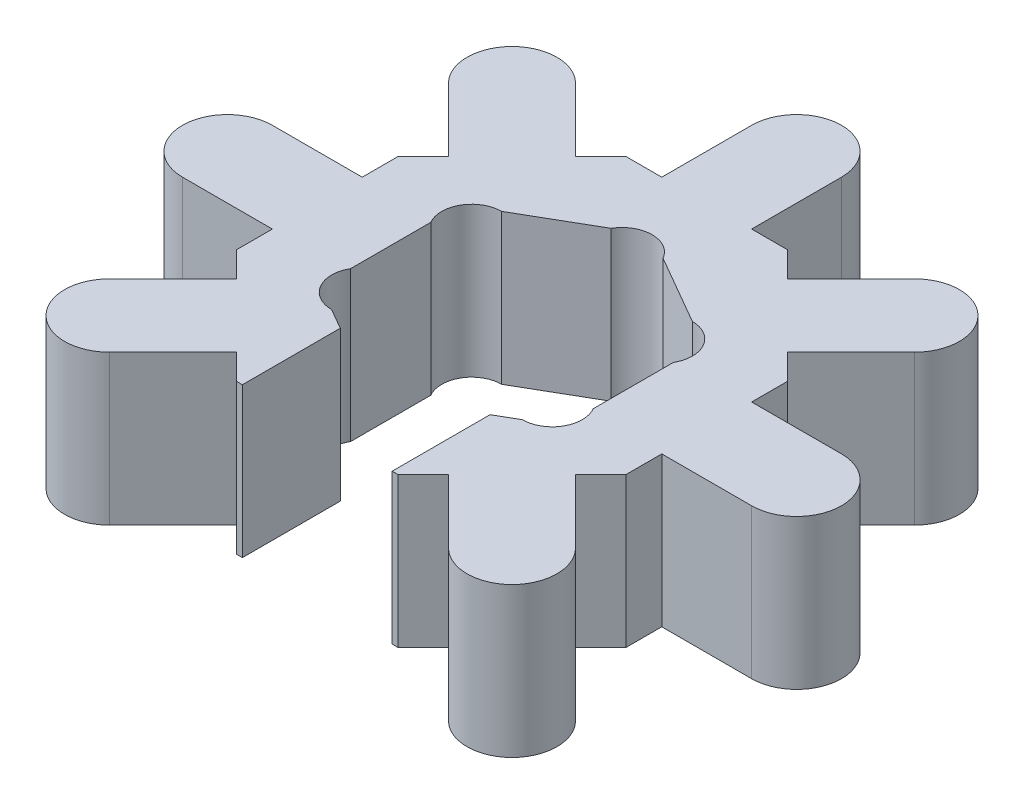
SolidWorks part; units mm, degrees
ref_plane "정면" through (0, 0, 0) normal (0, 0, 1) x (1, 0, 0)
ref_plane "윗면" through (0, 0, 0) normal (0, 1, 0) x (1, 0, 0)
ref_plane "우측면" through (0, 0, 0) normal (1, 0, 0) x (0, 0, -1)
sketch "스케치3" plane through (0, 0, 0) normal (0, 1, 0) x (1, 0, 0)
  line L1 (2.6924, 6.5) -> (-2.6924, 6.5)
  line L2 (-2.6924, 6.5) -> (-6.5, 2.6924)
  line L3 (-6.5, 2.6924) -> (-6.5, -2.6924)
  line L4 (-6.5, -2.6924) -> (-2.6924, -6.5)
  line L5 (-2.6924, -6.5) -> (2.6924, -6.5)
  line L6 (2.6924, -6.5) -> (6.5, -2.6924)
  line L7 (6.5, -2.6924) -> (6.5, 2.6924)
  line L8 (6.5, 2.6924) -> (2.6924, 6.5)
  circle A0 centre (0, 0) radius 6.5 construction
  dimension "D1" = 13
extrude "보스-돌출2" add sketch "스케치3" along normal blind 5
sketch "스케치4" plane through (0, 5, 0) normal (0, 1, 0) x (1, 0, 0)
  line L1 (4.05, 2.3383) -> (0, 4.6765)
  line L2 (0, 4.6765) -> (-4.05, 2.3383)
  line L3 (-4.05, 2.3383) -> (-4.05, -2.3383)
  line L4 (-4.05, -2.3383) -> (0, -4.6765)
  line L5 (0, -4.6765) -> (4.05, -2.3383)
  line L6 (4.05, -2.3383) -> (4.05, 2.3383)
  circle A0 centre (0, 0) radius 4.05 construction
  dimension "D1" = 8.1
extrude "컷-돌출1" cut sketch "스케치4" against normal blind 5
sketch "스케치5" plane through (0, 5, 0) normal (0, 1, 0) x (1, 0, 0)
  line L0 (0, 3.6765) -> (0, 4.6765) construction
  circle A0 centre (0, 3.6765) radius 1
  dimension "D1" = 2
extrude "컷-돌출2" cut sketch "스케치5" against normal blind 5
sketch3d "3D스케치1"
  line L0 (0, 0, 0) -> (0, -10, 0) construction
pattern_circular "원형 패턴1" count 6 over 360 about axis through (0, 0, 0) along (0, 1, 0) of "컷-돌출2"
sketch "스케치8" plane through (0, 5, 0) normal (0, 1, 0) x (1, 0, 0)
  line L0 (0, 0) -> (0, -9.6155) construction
  line L1 (2.5, 0) -> (2.5, -9.6155)
  line L2 (-2.5, 0) -> (-2.5, -9.6155)
  arc A0 (2.5, 0) -> (-2.5, 0) centre (0, 0) ccw
  arc A1 (-2.5, -9.6155) -> (2.5, -9.6155) centre (0, -9.6155) ccw
  point P3 (0, -4.8077)
  dimension "D1" = 2.5
extrude "컷-돌출3" cut sketch "스케치8" against normal blind 10
sketch "스케치9" plane through (0, 5, 0) normal (0, 1, 0) x (1, 0, 0)
  circle A0 centre (0, 0) radius 4.05 construction
sketch "스케치10" plane through (0, 5, 0) normal (0, 1, 0) x (1, 0, 0)
  line L0 (0, 0) -> (-4.5962, -4.5962) construction
  line L1 (-6.5, -2.6924) -> (-2.6924, -6.5) construction
  line L2 (-4.5962, -4.5962) -> (-6.7175, -6.7175) construction
  line L3 (-3.5355, -5.6569) -> (-5.6569, -7.7782)
  line L4 (-5.6569, -3.5355) -> (-7.7782, -5.6569)
  line L5 (-6.5, 0) -> (-9.5, 0) construction
  line L6 (-6.5, -1.5) -> (-9.5, -1.5)
  line L7 (-6.5, 1.5) -> (-9.5, 1.5)
  line L8 (-4.5962, 4.5962) -> (-6.7175, 6.7175) construction
  line L9 (-5.6569, 3.5355) -> (-7.7782, 5.6569)
  line L10 (-3.5355, 5.6569) -> (-5.6569, 7.7782)
  line L11 (0, 6.5) -> (0, 9.5) construction
  line L12 (-1.5, 6.5) -> (-1.5, 9.5)
  line L13 (1.5, 6.5) -> (1.5, 9.5)
  line L14 (4.5962, 4.5962) -> (6.7175, 6.7175) construction
  line L15 (3.5355, 5.6569) -> (5.6569, 7.7782)
  line L16 (5.6569, 3.5355) -> (7.7782, 5.6569)
  line L17 (6.5, 0) -> (9.5, 0) construction
  line L18 (6.5, 1.5) -> (9.5, 1.5)
  line L19 (6.5, -1.5) -> (9.5, -1.5)
  line L20 (4.5962, -4.5962) -> (6.7175, -6.7175) construction
  line L21 (5.6569, -3.5355) -> (7.7782, -5.6569)
  line L22 (3.5355, -5.6569) -> (5.6569, -7.7782)
  line L38 (0, -7.5) -> (0, -10.5) construction
  line L39 (1.5, -7.5) -> (1.5, -10.5)
  line L40 (-1.5, -7.5) -> (-1.5, -10.5)
  line L41 (0, -6.5) -> (0, -9.5) construction
  line L42 (1.5, -6.5) -> (1.5, -9.5)
  line L43 (-1.5, -6.5) -> (-1.5, -9.5)
  arc A0 (-3.5355, -5.6569) -> (-5.6569, -3.5355) centre (-4.5962, -4.5962) ccw
  arc A1 (-7.7782, -5.6569) -> (-5.6569, -7.7782) centre (-6.7175, -6.7175) ccw
  arc A2 (-6.5, -1.5) -> (-6.5, 1.5) centre (-6.5, 0) ccw
  arc A3 (-9.5, 1.5) -> (-9.5, -1.5) centre (-9.5, 0) ccw
  arc A4 (-5.6569, 3.5355) -> (-3.5355, 5.6569) centre (-4.5962, 4.5962) ccw
  arc A5 (-5.6569, 7.7782) -> (-7.7782, 5.6569) centre (-6.7175, 6.7175) ccw
  arc A6 (-1.5, 6.5) -> (1.5, 6.5) centre (0, 6.5) ccw
  arc A7 (1.5, 9.5) -> (-1.5, 9.5) centre (0, 9.5) ccw
  arc A8 (3.5355, 5.6569) -> (5.6569, 3.5355) centre (4.5962, 4.5962) ccw
  arc A9 (7.7782, 5.6569) -> (5.6569, 7.7782) centre (6.7175, 6.7175) ccw
  arc A10 (6.5, 1.5) -> (6.5, -1.5) centre (6.5, 0) ccw
  arc A11 (9.5, -1.5) -> (9.5, 1.5) centre (9.5, 0) ccw
  arc A12 (5.6569, -3.5355) -> (3.5355, -5.6569) centre (4.5962, -4.5962) ccw
  arc A13 (5.6569, -7.7782) -> (7.7782, -5.6569) centre (6.7175, -6.7175) ccw
  arc A26 (1.5, -6.5) -> (-1.5, -6.5) centre (0, -6.5) ccw
  arc A27 (-1.5, -9.5) -> (1.5, -9.5) centre (0, -9.5) ccw
  point P5 (-5.6569, -5.6569)
  point P15 (-8, 0)
  point P22 (-5.6569, 5.6569)
  point P29 (0, 8)
  point P36 (5.6569, 5.6569)
  point P43 (8, 0)
  point P50 (5.6569, -5.6569)
  point P57 (0, -11)
  point P63 (0, 0)
  point P66 (0, -11)
  point P73 (0, -9)
  point P80 (0, -9)
  point P87 (0, -9)
  point P94 (0, -9)
  point P101 (0, -8)
  dimension "D2" = 1.5
  dimension "D1" = 3
extrude "보스-돌출3" add sketch "스케치10" against normal blind 5
